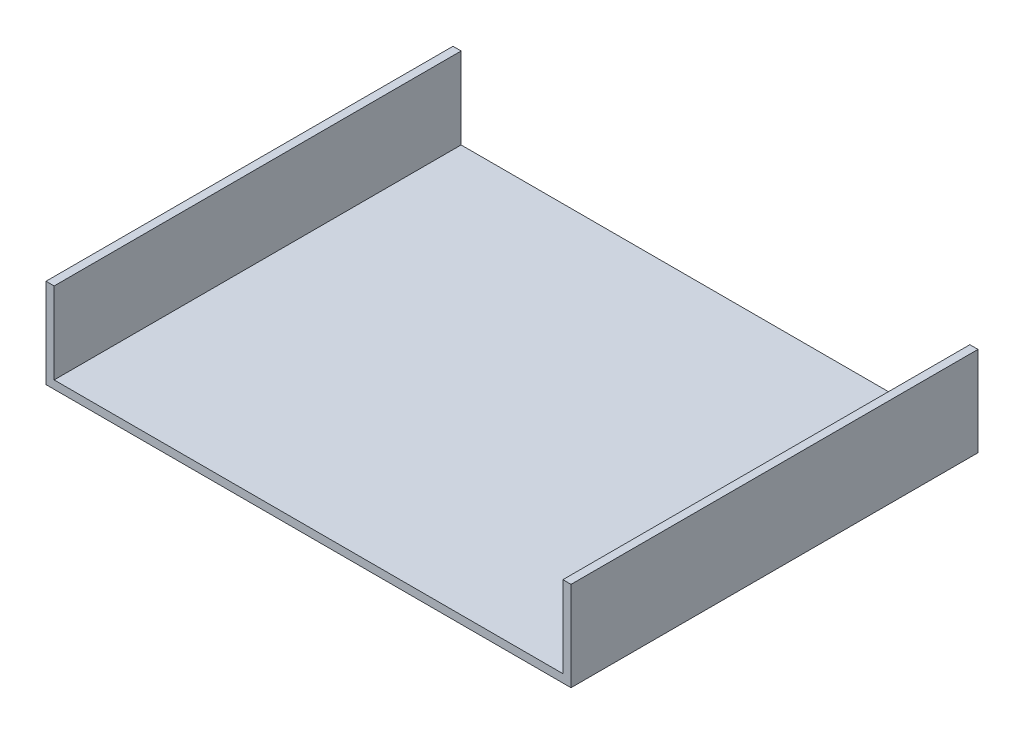
SolidWorks part; units mm, degrees
ref_plane "Front Plane" through (0, 0, 0) normal (0, 0, 1) x (1, 0, 0)
ref_plane "Top Plane" through (0, 0, 0) normal (0, 1, 0) x (1, 0, 0)
ref_plane "Right Plane" through (0, 0, 0) normal (1, 0, 0) x (0, 0, -1)
sketch "Sketch1" plane through (0, 0, 0) normal (0, 0, 1) x (1, 0, 0)
  line L0 (0, 0) -> (0, -2000)
  line L1 (0, -2000) -> (12500, -2000)
  line L2 (12500, -2000) -> (12500, 0)
  line L3 (-200, 0) -> (-200, -2200)
  line L4 (-200, -2200) -> (12700, -2200)
  line L5 (12700, -2200) -> (12700, 0)
  line L6 (-200, 0) -> (0, 0)
  line L7 (12500, 0) -> (12700, 0)
extrude "Boss-Extrude1" add sketch "Sketch1" along normal blind 10000
